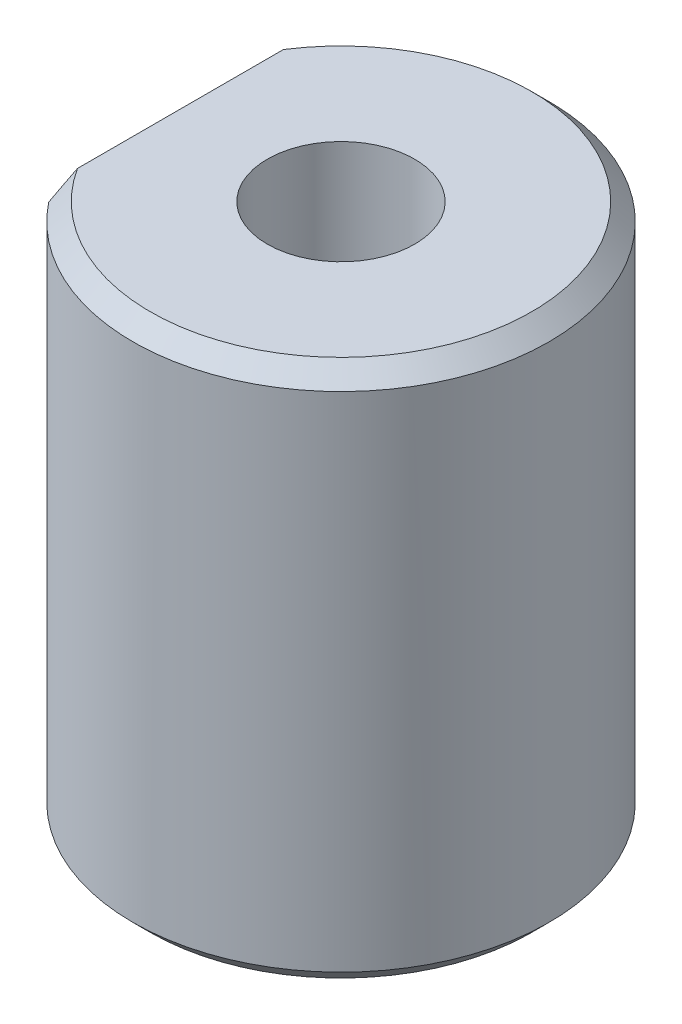
SolidWorks part; units mm, degrees
ref_plane "前视基准面" through (0, 0, 0) normal (0, 0, 1) x (1, 0, 0)
ref_plane "上视基准面" through (0, 0, 0) normal (0, 1, 0) x (1, 0, 0)
ref_plane "右视基准面" through (0, 0, 0) normal (1, 0, 0) x (0, 0, -1)
sketch "草图1" plane through (0, 0, 0) normal (0, 1, 0) x (1, 0, 0)
  circle A0 centre (0, 0) radius 12
  dimension "D1" = 24
extrude "凸台-拉伸1" add sketch "草图1" along normal blind 31
hole_wizard "M10 螺纹孔1" positions "草图3" profile "草图4" tap size "M10" standard "GB" end condition up to next
sketch "草图3" plane through (0, 31, 0) normal (0, 1, 0) x (1, 0, 0)
  point P0 (0, 0)
sketch "草图4" plane through (0, 31, 0) normal (1, 0, 0) x (0, 0, 1)
  line L0 (0, 0) -> (0, 31)
  line L1 (0, 31) -> (4.25, 31)
  line L2 (4.25, 31) -> (4.25, 0)
  line L5 (4.25, 0) -> (0, 0)
  line L11 (0, -6.35) -> (0, 107.95) construction
  dimension "通孔螺纹孔钻头直径" = 8.5
  dimension "通孔螺纹孔钻头深度" = 31
cosmetic thread "孔螺纹线1" parameters "D2"=10
chamfer "倒角1" distance 1 angle 45 2 edges at (0, 0, 12) (0, 31, 12)
sketch "草图5" plane through (0, 0, 0) normal (0, 0, 1) x (1, 0, 0)
  line L0 (12, 31) -> (-12, 31) construction
  circle A0 centre (-40, 35) radius 31
  dimension "D1" = 62
  dimension "D2" = 40
  dimension "D3" = 4
extrude "切除-拉伸1" cut sketch "草图5" against normal through all both and the other way through all
